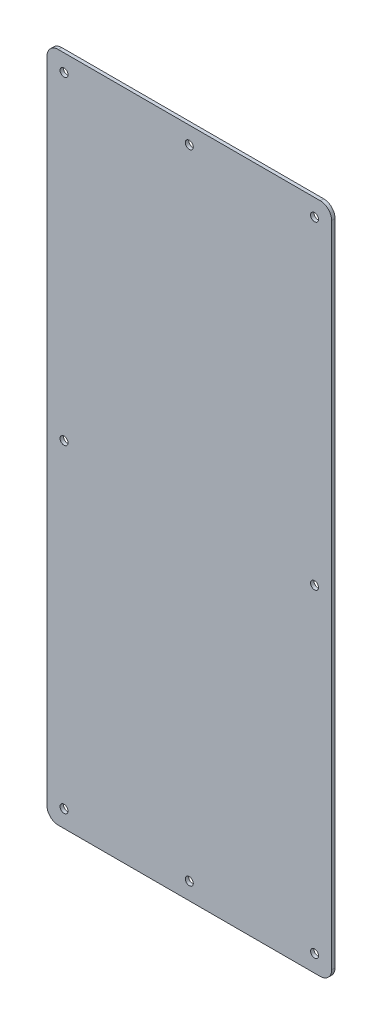
SolidWorks part; units mm, degrees
material "Q235"
ref_plane "前视基准面" through (0, 0, 0) normal (0, 0, 1) x (1, 0, 0)
ref_plane "上视基准面" through (0, 0, 0) normal (0, 1, 0) x (1, 0, 0)
ref_plane "右视基准面" through (0, 0, 0) normal (1, 0, 0) x (0, 0, -1)
sketch "草图1" plane through (0, 0, 0) normal (0, 0, 1) x (1, 0, 0)
  line L1 (-125, 295) -> (125, 295)
  line L2 (-125, 295) -> (-125, -295)
  line L3 (-125, -295) -> (125, -295)
  line L4 (125, 295) -> (125, -295)
  line L5 (-125, 295) -> (125, -295) construction
  line L6 (-125, -295) -> (125, 295) construction
  point P0 (0, 0)
  dimension "D1" = 250
  dimension "D2" = 590
extrude "凸台-拉伸1" add sketch "草图1" along normal blind 3
fillet "圆角1" radius 10 4 edges at (125, -295, 1.5) (-125, -295, 1.5) (-125, 295, 1.5) (125, 295, 1.5)
sketch "草图3" plane through (0, 0, 3) normal (0, 0, 1) x (1, 0, 0)
  line L0 (115, 295) -> (-115, 295) construction
  line L1 (-125, 285) -> (-125, -285) construction
  line L2 (125, -285) -> (125, 285) construction
  line L3 (-115, -295) -> (115, -295) construction
  line L4 (1.65, 0) -> (-1.65, 0) construction
  line L5 (0, -1.65) -> (0, 1.65) construction
  circle A0 centre (-110, 280) radius 3.5
  circle A1 centre (-110, -280) radius 3.5
  circle A2 centre (110, 280) radius 3.5
  circle A3 centre (110, -280) radius 3.5
  circle A4 centre (-110, 0) radius 3.5
  circle A5 centre (110, 0) radius 3.5
  circle A6 centre (0, 280) radius 3.5
  circle A7 centre (0, -280) radius 3.5
  dimension "D1" = 7
  dimension "D2" = 15
  dimension "D3" = 15
  dimension "D4" = 15
  dimension "D5" = 15
  dimension "D6" = 15
  dimension "D7" = 15
  dimension "D8" = 15
  dimension "D9" = 15
  dimension "D10" = 15
  dimension "D11" = 7
  dimension "D12" = 7
  dimension "D13" = 15
  dimension "D14" = 7
  dimension "D15" = 15
  dimension "D16" = 15
extrude "切除-拉伸1" cut sketch "草图3" against normal blind 3
